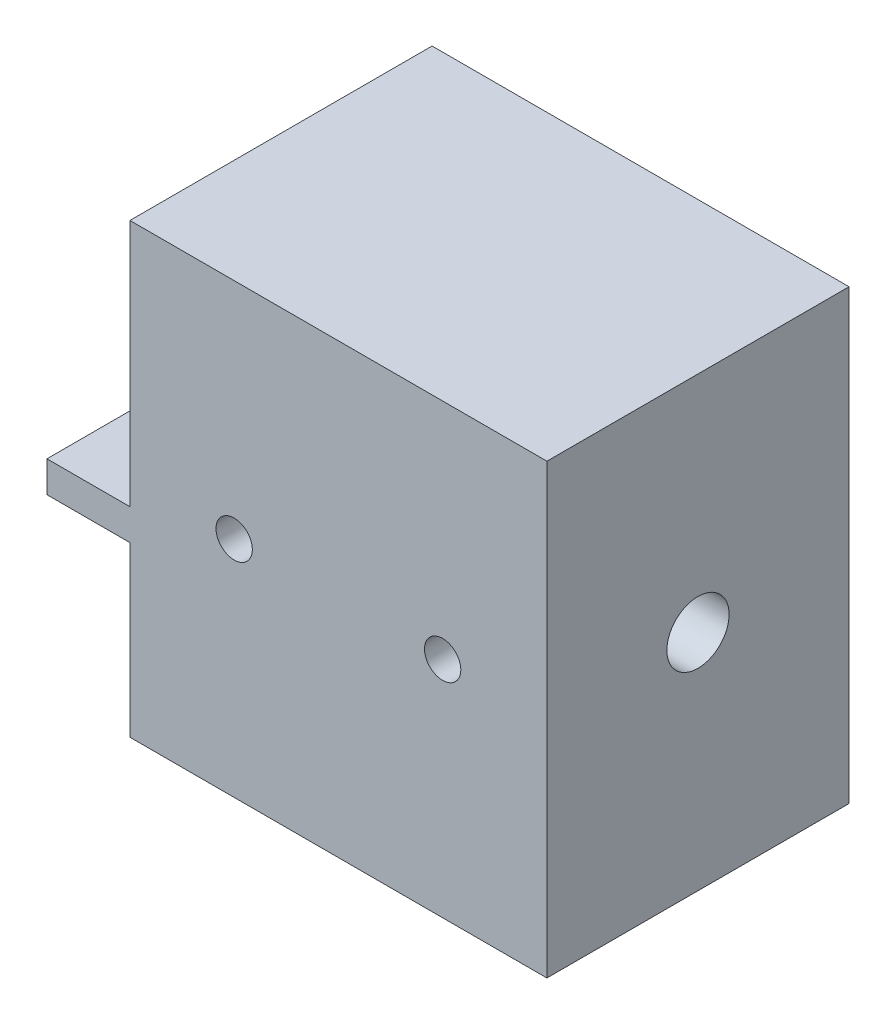
SolidWorks part; units mm, degrees
ref_plane "Front Plane" through (0, 0, 0) normal (0, 0, 1) x (1, 0, 0)
ref_plane "Top Plane" through (0, 0, 0) normal (0, 1, 0) x (1, 0, 0)
ref_plane "Right Plane" through (0, 0, 0) normal (1, 0, 0) x (0, 0, -1)
sketch "Sketch2" plane through (0, 0, 0) normal (0, 0, 1) x (1, 0, 0)
  line L1 (-50.4013, 17.7812) -> (-10.2013, 17.7812)
  line L2 (-50.4013, 17.7812) -> (-50.4013, -25.3688)
  line L3 (-50.4013, -25.3688) -> (-10.2013, -25.3688)
  line L4 (-10.2013, 17.7812) -> (-10.2013, -25.3688)
extrude "Boss-Extrude1" add sketch "Sketch2" along normal blind 29.13
sketch "Sketch3" plane through (-50.4013, 0, 0) normal (-1, 0, 0) x (0, 0, 1)
  line L0 (0, -9.1188) -> (0, -6.1188)
  line L1 (0, 17.7812) -> (0, -25.3688) construction
  line L2 (0, -9.1188) -> (29.13, -9.1188) construction
  line L3 (29.13, 17.7812) -> (29.13, -25.3688) construction
  line L4 (0, -6.1188) -> (29.13, -6.1188)
  line L5 (29.13, -6.1188) -> (29.13, -9.1188)
  line L10 (29.13, -9.1188) -> (0, -9.1188)
extrude "Boss-Extrude2" add sketch "Sketch3" along normal blind 8
sketch "Sketch4" plane through (0, -9.1188, 0) normal (0, 1, 0) x (1, 0, 0)
  circle A0 centre (-53.6013, -9.375) radius 1.75
  circle A1 centre (-53.6013, -19.725) radius 1.75
extrude "Cut-Extrude1" cut sketch "Sketch4" against normal blind 8 and the other way blind 8
sketch "Sketch5" plane through (0, 0, 0) normal (0, 0, -1) x (-1, 0, 0)
  line L0 (10.2013, -3.7938) -> (50.4013, -3.7938) construction
  line L1 (10.2013, -25.3688) -> (10.2013, 17.7812) construction
  line L2 (50.4013, 17.7812) -> (50.4013, -6.1188) construction
  line L3 (50.4013, -3.7938) -> (30.3013, -3.7938) construction
  line L4 (10.2013, -3.7938) -> (30.3013, -3.7938) construction
  circle A0 centre (40.3513, -3.7938) radius 1.75
  circle A1 centre (20.2513, -3.7938) radius 1.75
extrude "Cut-Extrude2" cut sketch "Sketch5" against normal blind 40
sketch "Sketch6" plane through (-10.2013, 0, 0) normal (1, 0, 0) x (0, 0, -1)
  line L0 (-14.565, 17.7812) -> (-14.565, -25.3688) construction
  line L1 (-29.13, 17.7812) -> (0, 17.7812) construction
  line L2 (-29.13, -25.3688) -> (0, -25.3688) construction
  circle A0 centre (-14.565, -3.7938) radius 3
extrude "Cut-Extrude3" cut sketch "Sketch6" against normal blind 18
